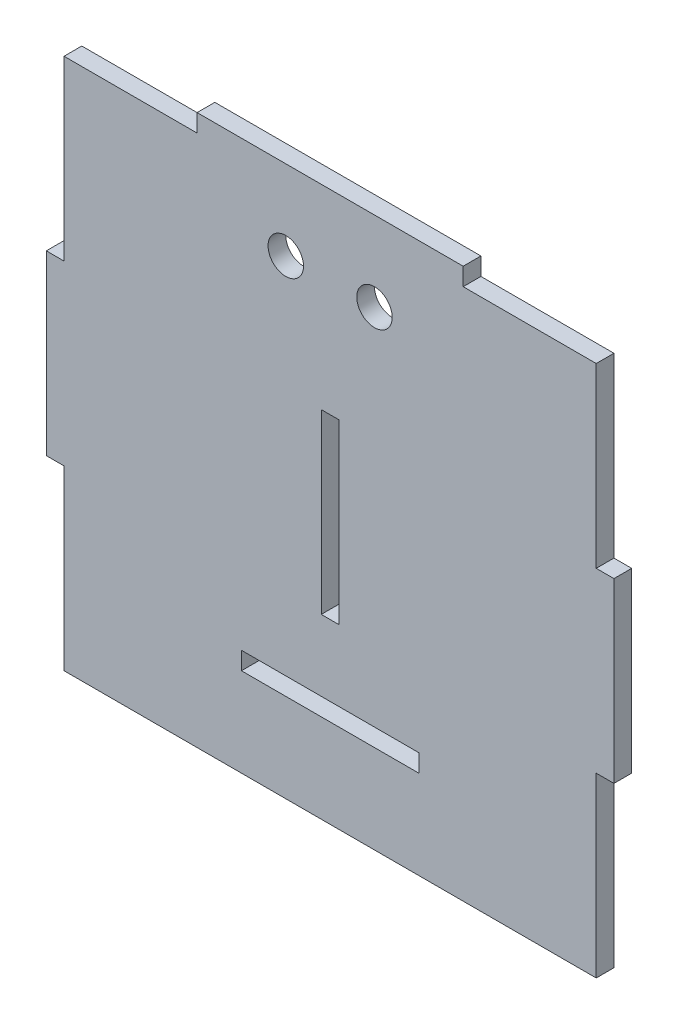
SolidWorks part; units mm, degrees
ref_plane "前视基准面" through (0, 0, 0) normal (0, 0, 1) x (1, 0, 0)
ref_plane "上视基准面" through (0, 0, 0) normal (0, 1, 0) x (1, 0, 0)
ref_plane "右视基准面" through (0, 0, 0) normal (1, 0, 0) x (0, 0, -1)
sketch "草图2" plane through (0, 0, 0) normal (0, 0, 1) x (1, 0, 0)
  line L0 (0, 60) -> (0, 0)
  line L1 (0, 60) -> (60, 60)
  line L2 (0, 0) -> (60, 0)
  line L3 (60, 60) -> (60, 0)
  line L4 (15, 62) -> (15, 60)
  line L5 (15, 62) -> (45, 62)
  line L6 (15, 60) -> (45, 60)
  line L7 (45, 62) -> (45, 60)
  line L8 (-2, 40) -> (-2, 20)
  line L9 (-2, 40) -> (0, 40)
  line L10 (-2, 20) -> (0, 20)
  line L11 (0, 40) -> (0, 20)
  line L12 (60, 40) -> (62, 40)
  line L13 (60, 40) -> (60, 20)
  line L14 (62, 40) -> (62, 20)
  line L15 (60, 20) -> (62, 20)
  line L16 (20, 12) -> (20, 10)
  line L17 (20, 12) -> (40, 12)
  line L18 (20, 10) -> (40, 10)
  line L19 (40, 12) -> (40, 10)
  line L20 (29, 40) -> (29, 20)
  line L21 (29, 40) -> (31, 40)
  line L22 (29, 20) -> (31, 20)
  line L23 (31, 40) -> (31, 20)
  circle A0 centre (25, 53) radius 2
  circle A1 centre (35, 53) radius 2
  point P0 (25, 53)
  point P3 (35, 53)
  point P8 (15, 62)
  point P11 (45, 62)
  point P12 (15, 60)
  point P13 (45, 60)
  point P14 (-2, 40)
  point P15 (-2, -10)
  point P16 (-2, 20)
  point P17 (0, 20)
  point P18 (0, 40)
  point P19 (60, 40)
  point P20 (60, 20)
  point P21 (62, 40)
  point P22 (62, 20)
  point P23 (20, 12)
  point P30 (20, 10)
  point P31 (40, 12)
  point P32 (40, 10)
extrude "凸台-拉伸1" add sketch "草图2" along normal blind 2 contours L8 L10 L0 L9 | L7 L5 L4 L1 | L3 L1 L0 L2 A1 A0 L17 L19 L18 L16 | L3 L15 L14 L12
